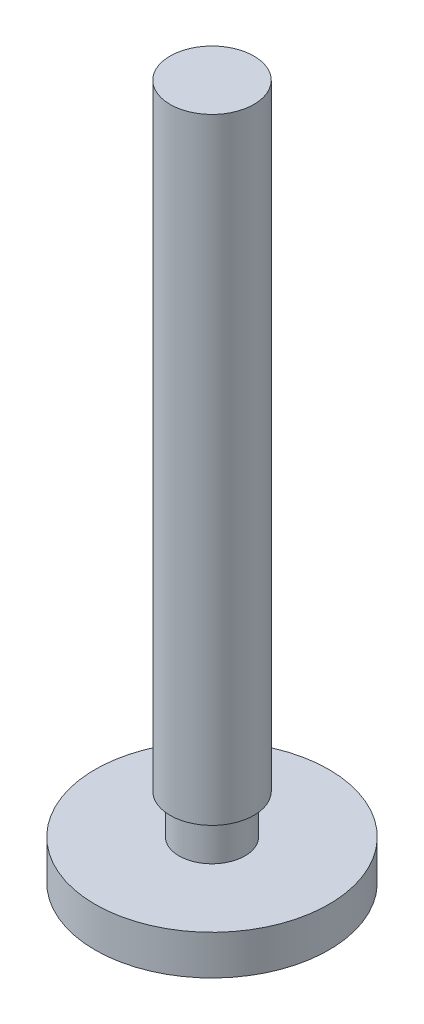
SolidWorks part; units mm, degrees
ref_plane "Alzado" through (0, 0, 0) normal (0, 0, 1) x (1, 0, 0)
ref_plane "Planta" through (0, 0, 0) normal (0, 1, 0) x (1, 0, 0)
ref_plane "Vista lateral" through (0, 0, 0) normal (1, 0, 0) x (0, 0, -1)
sketch "Croquis1" plane through (0, 0, 0) normal (0, 0, 1) x (1, 0, 0)
  line L0 (8.75, 2.25) -> (-8.75, -2.25) construction
  line L1 (-8.75, 2.25) -> (8.75, 2.25)
  line L3 (-4.25, -2.25) -> (4.25, -2.25)
  line L5 (0, 0) -> (0, -2.25) construction
  line L6 (-8.75, 2.25) -> (-4.25, -2.25)
  line L7 (-4.25, -2.25) -> (-4.2403, -2.2053)
  line L8 (4.25, -2.25) -> (8.75, 2.25)
  dimension "D1" = 45
  dimension "D2" = 4.5
  dimension "D3" = 4.25
  dimension "D4" = 4.25
  dimension "D5" = 17.5
extrude "Saliente-Extruir1" add sketch "Croquis1" along normal blind 20
sketch "Croquis2" plane through (0, 2.25, 0) normal (0, 1, 0) x (1, 0, 0)
  line L0 (0, -10) -> (8.75, -10) construction
  line L1 (8.75, -20) -> (8.75, 0) construction
  line L2 (0, 0) -> (0, -10) construction
  circle A0 centre (0, -10) radius 3.75
  dimension "D1" = 7.5
extrude "Cortar-Extruir1" cut sketch "Croquis2" against normal up to next
sketch "Croquis3" plane through (0, -2.25, 0) normal (0, -1, 0) x (1, 0, 0)
  circle A0 centre (0, 10) radius 3.75
extrude "Saliente-Extruir2" add sketch "Croquis3" against normal blind 9
sketch "Croquis4" plane through (0, 6.75, 0) normal (0, 1, 0) x (1, 0, 0)
  circle A0 centre (0, -10) radius 4.765
  dimension "D1" = 9.53
extrude "Saliente-Extruir3" add sketch "Croquis4" along normal blind 70
sketch "Croquis5" plane through (0, 2.25, 0) normal (0, 1, 0) x (1, 0, 0)
  circle A0 centre (0, -10) radius 13.2877
  dimension "D1" = 26.5754
extrude "Saliente-Extruir4" add sketch "Croquis5" against normal up to surface (4.5 mm away) up to face at (0, -2.25, 10)
